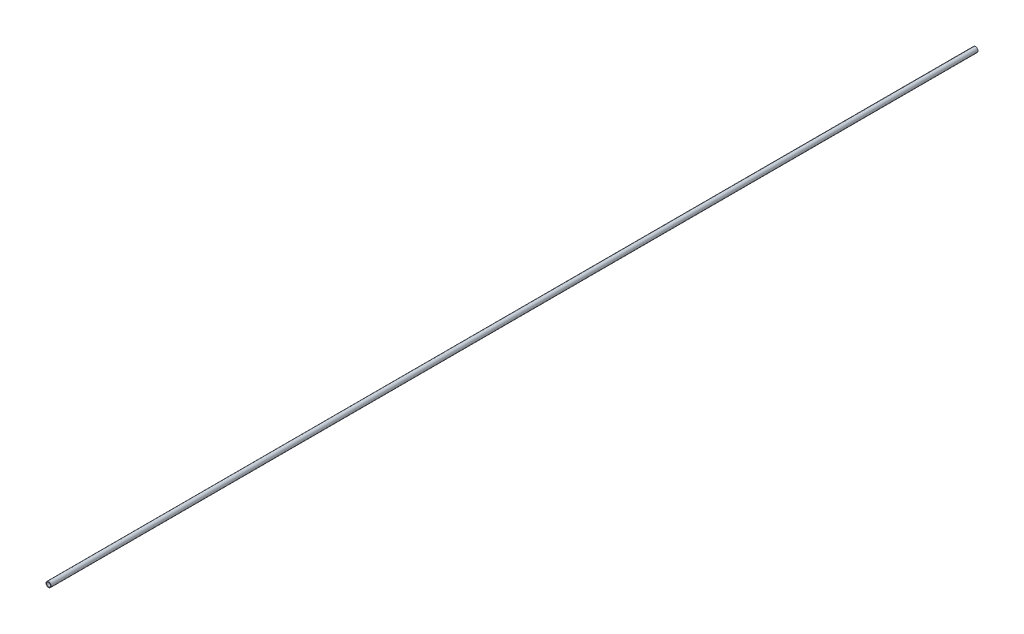
SolidWorks part; units mm, degrees
material "Plain Carbon Steel"
ref_plane "Plane1" through (0, 0, 0) normal (0, 0, 1) x (1, 0, 0)
ref_plane "Plane2" through (0, 0, 0) normal (0, 1, 0) x (1, 0, 0)
ref_plane "Plane3" through (0, 0, 0) normal (1, 0, 0) x (0, 0, -1)
sketch "Sketch1" plane through (0, 0, 0) normal (0, 0, 1) x (1, 0, 0)
  circle A0 centre (0, 0) radius 13.3223
  circle A1 centre (0, 0) radius 16.7005
extrude "BasePipe" add sketch "Sketch1" along normal mid plane 6096
sketch "Sketch10" plane through (0, 0, 0) normal (1, 0, 0) x (0, 0, -1)
  line L0 (-3048.5857, 0) -> (-3090.2803, 0) construction
  line L1 (3048, 16.7005) -> (-3048, 16.7005) construction
  line L2 (-3048, 16.7005) -> (-3048, -16.7005) construction
  point P2 (-3025.775, 16.7005)
  dimension "D1" = 22.225
ref_plane "Plane4" through (0, 0, 3025.775) normal (0, 0, 1) x (1, 0, 0)
sketch "Sketch11" plane through (0, 0, 3025.775) normal (0, 0, 1) x (1, 0, 0)
  circle A0 centre (0, 0) radius 16.7005 construction
  circle A1 centre (0, 0) radius 16.7005
curve "Helix/Spiral2" pitch 2.2087 height 22.087 turns 10
sketch "Sketch14" plane through (0, 0, 0) normal (1, 0, 0) x (0, 0, -1)
  line L0 (0, -6.1404) -> (2.317, -2.1272)
  line L1 (2.317, -2.1272) -> (2.317, 6.1404)
  line L2 (2.317, 6.1404) -> (-2.317, 6.1404)
  line L3 (0, -6.1404) -> (-2.317, -2.1272)
  line L4 (-2.317, -2.1272) -> (-2.317, 6.1404)
  line L5 (2.317, -6.1404) -> (2.317, -2.1272) construction
  line L6 (2.317, -6.1404) -> (0, -6.1404) construction
  line L7 (-3047.862, 10.5601) -> (-3045.5449, 14.5733)
  line L8 (-3045.5449, 14.5733) -> (-3045.5449, 23.2351)
  line L9 (-3045.5449, 23.2351) -> (-3050.179, 23.2351)
  line L10 (-3047.862, 10.5601) -> (-3050.179, 14.5733)
  line L11 (-3050.179, 14.5733) -> (-3050.179, 23.2351)
  line L12 (-3045.5449, 10.5601) -> (-3045.5449, 14.5733) construction
  line L13 (-3045.5449, 10.5601) -> (-3047.862, 10.5601) construction
  line L14 (-3050.179, 14.5733) -> (-3045.5449, 14.5733) construction
  line L15 (-3047.862, 10.5601) -> (-3047.862, 14.5733) construction
  point P6 (0, 6.1404)
  point P13 (-3047.862, 23.2351)
